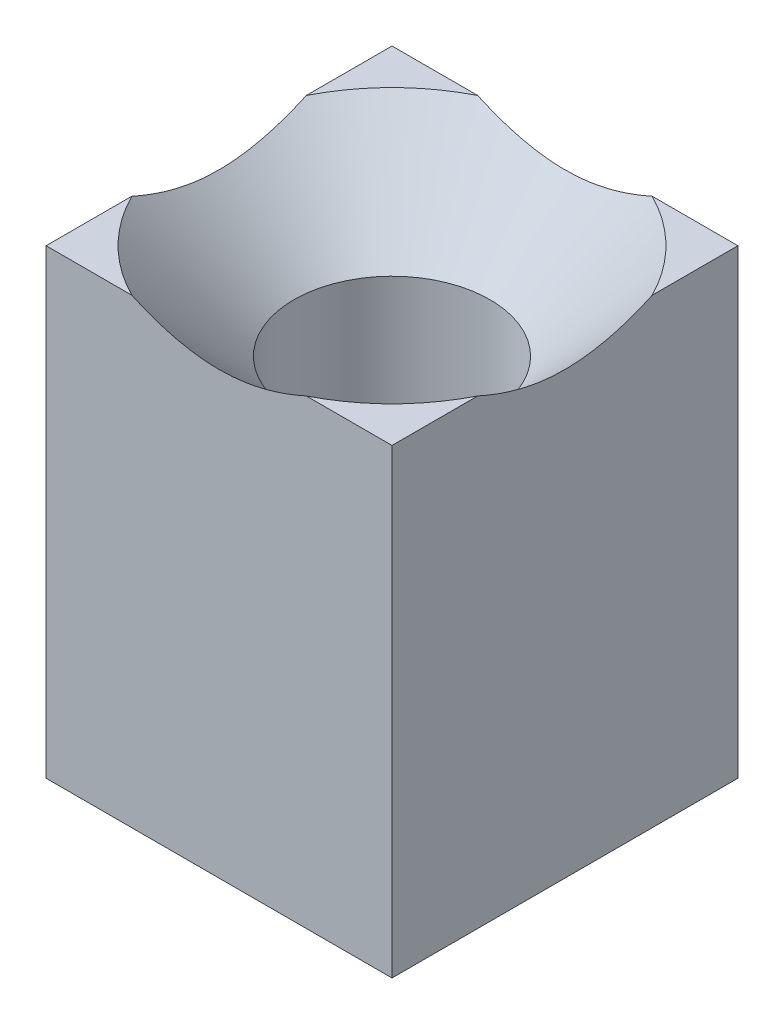
SolidWorks part; units mm, degrees
ref_plane "前视基准面" through (0, 0, 0) normal (0, 0, 1) x (1, 0, 0)
ref_plane "上视基准面" through (0, 0, 0) normal (0, 1, 0) x (1, 0, 0)
ref_plane "右视基准面" through (0, 0, 0) normal (1, 0, 0) x (0, 0, -1)
sketch "Sketch1" plane through (0, 0, 0) normal (0, 1, 0) x (1, 0, 0)
  line L1 (3, -3) -> (-3, -3)
  line L2 (3, -3) -> (3, 3)
  line L3 (3, 3) -> (-3, 3)
  line L4 (-3, -3) -> (-3, 3)
  line L5 (3, -3) -> (-3, 3) construction
  line L6 (3, 3) -> (-3, -3) construction
  circle A0 centre (0, 0) radius 1.5
  point P0 (0, 0)
  dimension "D1" = 6
  dimension "D2" = 6
extrude "Boss-Extrude1" add sketch "Sketch1" along normal blind 8
hole_wizard "CSK for M3 SFHCS1" positions "Sketch2" profile "Sketch3" countersink size "M3" standard "ANSI Metric"
sketch "Sketch2" plane through (0, 8, 0) normal (0, 1, 0) x (1, 0, 0)
  point P0 (0, 0)
sketch "Sketch3" plane through (0, 8, 0) normal (1, 0, 0) x (0, 0, 1)
  line L0 (0, 0) -> (0, 12.3215)
  line L1 (0, 12.3215) -> (1.7, 11.3)
  line L2 (1.7, 11.3) -> (1.7, 1.66)
  line L3 (1.7, 1.66) -> (3.36, 0)
  line L5 (3.36, 0) -> (0, 0)
  line L6 (-1.7, 1.66) -> (-3.36, 0) construction
  line L10 (0, 12.3215) -> (-1.7, 11.3) construction
  line L11 (0, -6.35) -> (0, 107.95) construction
  dimension "Hole Dia." = 3.4
  dimension "Hole Depth" = 11.3
  dimension "Near C'Sink Dia." = 6.72
  dimension "Near C'Sink Angle" = 90
  dimension "Drill Angle" = 118
